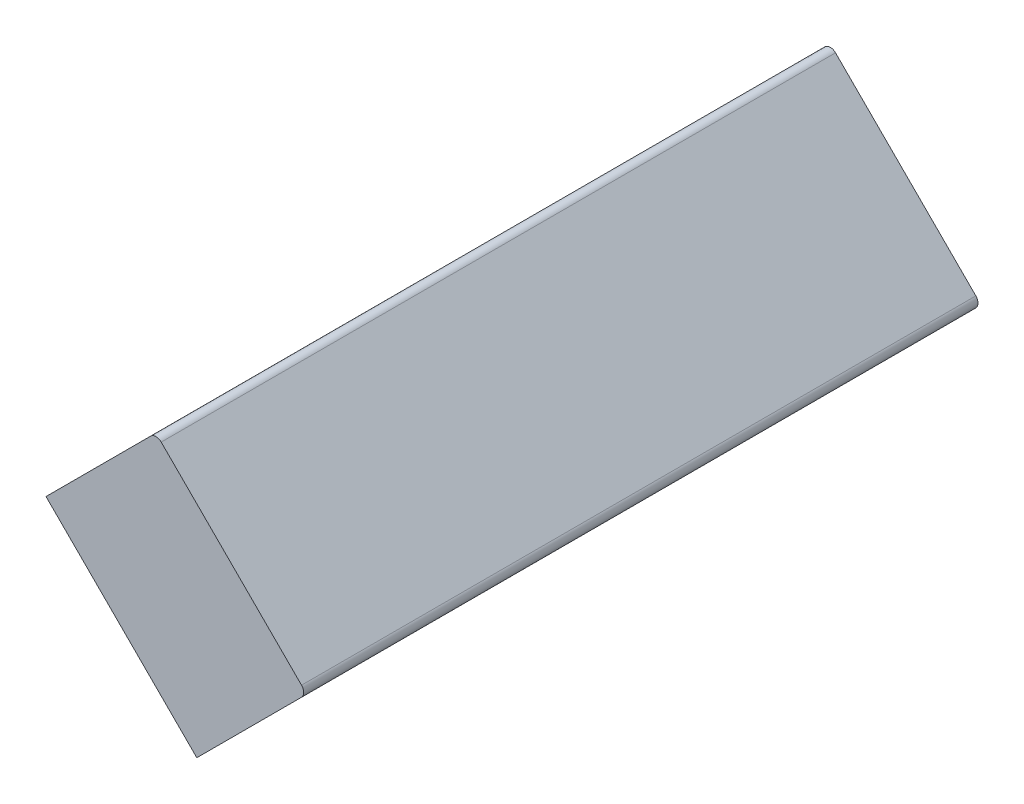
SolidWorks part; units mm, degrees
ref_plane "Front Plane" through (0, 0, 0) normal (0, 0, 1) x (1, 0, 0)
ref_plane "Top Plane" through (0, 0, 0) normal (0, 1, 0) x (1, 0, 0)
ref_plane "Right Plane" through (0, 0, 0) normal (1, 0, 0) x (0, 0, -1)
other "Configuration Table"
sketch "Sketch1" plane through (0, 0, 0) normal (0, 0, 1) x (1, 0, 0)
  line L0 (115.223, 217.0464) -> (217.0464, 115.223)
  line L1 (217.0464, 115.223) -> (287.7571, 185.9337)
  line L2 (287.7571, 193.0048) -> (193.0048, 287.7571)
  line L3 (185.9337, 287.7571) -> (115.223, 217.0464)
  arc A0 (287.7571, 185.9337) -> (287.7571, 193.0048) centre (284.2216, 189.4693) ccw
  arc A1 (193.0048, 287.7571) -> (185.9337, 287.7571) centre (189.4693, 284.2216) ccw
extrude "Head Casting" add sketch "Sketch1" along normal blind 455.28 from offset 383.38
sketch "Sketch2" plane through (0, 0, 0) normal (0, 0, 1) x (1, 0, 0)
  line L0 (135.7291, 238.9667) -> (153.4068, 221.2891)
  line L1 (161.8921, 221.2891) -> (181.6911, 241.0881)
  line L2 (181.6911, 249.5733) -> (164.0134, 267.251)
  line L3 (164.0134, 267.251) -> (135.7291, 238.9667)
  arc A0 (153.4068, 221.2891) -> (161.8921, 221.2891) centre (157.6495, 225.5317) ccw
  arc A1 (181.6911, 241.0881) -> (181.6911, 249.5733) centre (177.4484, 245.3307) ccw
extrude "Intake Port 1" cut sketch "Sketch2" along normal blind 28 from offset 2.1
sketch "Sketch3" plane through (0, 0, 0) normal (0, 0, 1) x (1, 0, 0)
  line L0 (240.381, 137.1434) -> (224.1175, 153.4068)
  line L1 (224.1175, 164.7205) -> (238.2596, 178.8627)
  line L2 (249.5733, 178.8627) -> (265.8368, 162.5992)
  line L3 (265.8368, 162.5992) -> (240.381, 137.1434)
  arc A0 (224.1175, 153.4068) -> (224.1175, 164.7205) centre (229.7743, 159.0637) cw
  arc A1 (238.2596, 178.8627) -> (249.5733, 178.8627) centre (243.9165, 173.2058) cw
extrude "Exhaust Port 1" cut sketch "Sketch3" along normal blind 32 from offset 4.1
sketch "Sketch4" plane through (0, 0, 0) normal (0, 0, 1) x (1, 0, 0)
  line L0 (135.7291, 238.9667) -> (153.4068, 221.2891)
  line L1 (161.8921, 221.2891) -> (181.6911, 241.0881)
  line L2 (181.6911, 249.5733) -> (164.0134, 267.251)
  line L3 (164.0134, 267.251) -> (135.7291, 238.9667)
  arc A0 (153.4068, 221.2891) -> (161.8921, 221.2891) centre (157.6495, 225.5317) ccw
  arc A1 (181.6911, 241.0881) -> (181.6911, 249.5733) centre (177.4484, 245.3307) ccw
extrude "Intake Port 3" cut sketch "Sketch4" along normal blind 28 from offset 113.86
sketch "Sketch5" plane through (0, 0, 0) normal (0, 0, 1) x (1, 0, 0)
  line L0 (240.381, 137.1434) -> (224.1175, 153.4068)
  line L1 (224.1175, 164.7205) -> (238.2596, 178.8627)
  line L2 (249.5733, 178.8627) -> (265.8368, 162.5992)
  line L3 (265.8368, 162.5992) -> (240.381, 137.1434)
  arc A0 (224.1175, 153.4068) -> (224.1175, 164.7205) centre (229.7743, 159.0637) cw
  arc A1 (238.2596, 178.8627) -> (249.5733, 178.8627) centre (243.9165, 173.2058) cw
extrude "Exhaust Port 3" cut sketch "Sketch5" along normal blind 32 from offset 115.86
sketch "Sketch6" plane through (0, 0, 0) normal (0, 0, 1) x (1, 0, 0)
  line L0 (135.7291, 238.9667) -> (153.4068, 221.2891)
  line L1 (161.8921, 221.2891) -> (181.6911, 241.0881)
  line L2 (181.6911, 249.5733) -> (164.0134, 267.251)
  line L3 (164.0134, 267.251) -> (135.7291, 238.9667)
  arc A0 (153.4068, 221.2891) -> (161.8921, 221.2891) centre (157.6495, 225.5317) ccw
  arc A1 (181.6911, 241.0881) -> (181.6911, 249.5733) centre (177.4484, 245.3307) ccw
extrude "Intake Port 5" cut sketch "Sketch6" along normal blind 28 from offset 225.62
sketch "Sketch7" plane through (0, 0, 0) normal (0, 0, 1) x (1, 0, 0)
  line L0 (240.381, 137.1434) -> (224.1175, 153.4068)
  line L1 (224.1175, 164.7205) -> (238.2596, 178.8627)
  line L2 (249.5733, 178.8627) -> (265.8368, 162.5992)
  line L3 (265.8368, 162.5992) -> (240.381, 137.1434)
  arc A0 (224.1175, 153.4068) -> (224.1175, 164.7205) centre (229.7743, 159.0637) cw
  arc A1 (238.2596, 178.8627) -> (249.5733, 178.8627) centre (243.9165, 173.2058) cw
extrude "Exhaust Port 5" cut sketch "Sketch7" along normal blind 32 from offset 227.62
sketch "Sketch8" plane through (0, 0, 0) normal (0, 0, 1) x (1, 0, 0)
  line L0 (135.7291, 238.9667) -> (153.4068, 221.2891)
  line L1 (161.8921, 221.2891) -> (181.6911, 241.0881)
  line L2 (181.6911, 249.5733) -> (164.0134, 267.251)
  line L3 (164.0134, 267.251) -> (135.7291, 238.9667)
  arc A0 (153.4068, 221.2891) -> (161.8921, 221.2891) centre (157.6495, 225.5317) ccw
  arc A1 (181.6911, 241.0881) -> (181.6911, 249.5733) centre (177.4484, 245.3307) ccw
extrude "Intake Port 7" cut sketch "Sketch8" along normal blind 28 from offset 337.38
sketch "Sketch9" plane through (0, 0, 0) normal (0, 0, 1) x (1, 0, 0)
  line L0 (240.381, 137.1434) -> (224.1175, 153.4068)
  line L1 (224.1175, 164.7205) -> (238.2596, 178.8627)
  line L2 (249.5733, 178.8627) -> (265.8368, 162.5992)
  line L3 (265.8368, 162.5992) -> (240.381, 137.1434)
  arc A0 (224.1175, 153.4068) -> (224.1175, 164.7205) centre (229.7743, 159.0637) cw
  arc A1 (238.2596, 178.8627) -> (249.5733, 178.8627) centre (243.9165, 173.2058) cw
extrude "Exhaust Port 7" cut sketch "Sketch9" along normal blind 32 from offset 339.38
